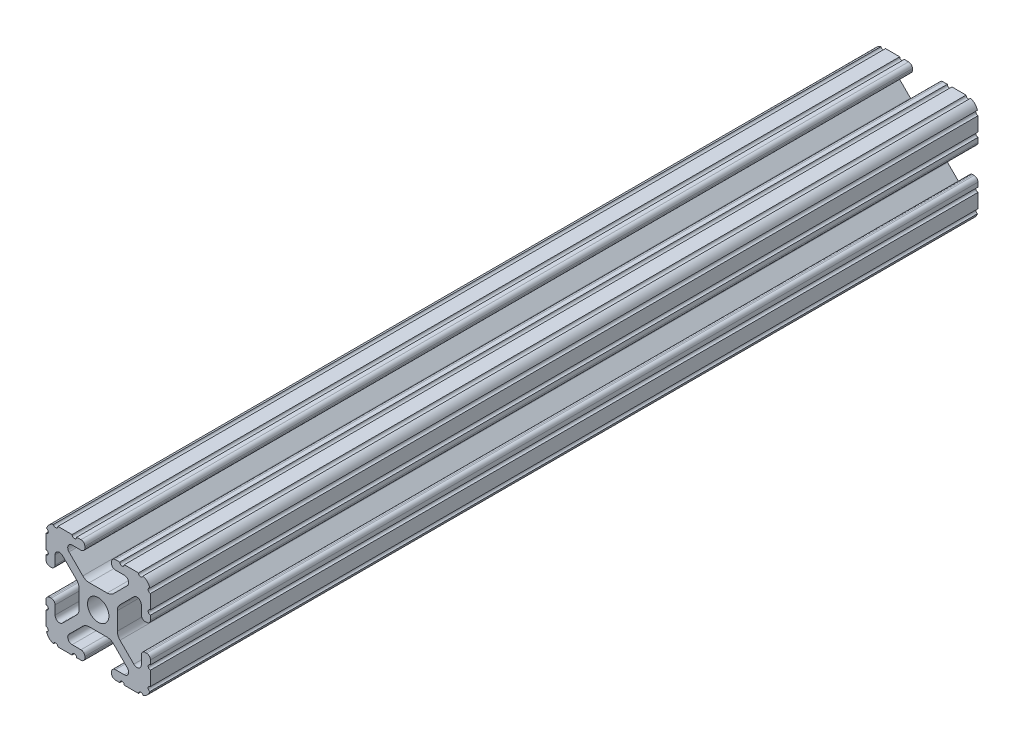
SolidWorks part; units mm, degrees
ref_plane "Front Plane" through (0, 0, 0) normal (0, 0, 1) x (1, 0, 0)
ref_plane "Top Plane" through (0, 0, 0) normal (0, 1, 0) x (1, 0, 0)
ref_plane "Right Plane" through (0, 0, 0) normal (1, 0, 0) x (0, 0, -1)
sketch "Sketch2" plane through (0, 0, 0) normal (0, 0, 1) x (1, 0, 0)
  line L0 (0, 12.7) -> (0, -12.7) construction
  line L1 (-12.7, 0) -> (12.7, 0) construction
  line L2 (3.2512, -12.7) -> (12.7, -12.7)
  line L3 (12.7, -12.7) -> (12.7, -3.2512)
  line L4 (3.2512, -12.7) -> (3.2512, -10.4902)
  line L5 (3.2512, -10.4902) -> (8.9276, -10.4902)
  line L6 (8.9276, -10.4902) -> (3.0856, -4.6482)
  line L7 (0, 0) -> (12.7, -12.7) construction
  line L8 (12.7, -3.2512) -> (10.4902, -3.2512)
  line L9 (10.4902, -3.2512) -> (10.4902, -8.9276)
  line L10 (10.4902, -8.9276) -> (4.6482, -3.0856)
  circle A0 centre (0, 0) radius 2.6035
  arc A1 (6.3485, -10.4902) -> (7.1039, -8.6665) centre (6.3485, -9.4219) ccw construction
  point P8 (0, -4.6482)
  dimension "Center Hole Diameter" = 5.207
  dimension "Rail Height" = 25.4
  dimension "Rail Width" = 25.4
  dimension "T-Slot Width" = 6.5024
  dimension "Slot Inner Width" = 14.8336
  dimension "Thickness" = 2.2098
  dimension "Slot Depth" = 5.842
  dimension "D1" = 2.2098
sketch "Sketch3" plane through (0, 0, 0) normal (1, 0, 0) x (0, 0, -1)
  line L0 (-100.6793, -12.7) -> (100.6793, -12.7) construction
  line L1 (-75.2793, 0) -> (75.2793, 0) construction
  line L4 (100.6793, 0) -> (-100.6793, 0) construction
sketch "Sketch4" plane through (0, 0, 0) normal (0, 0, 1) x (1, 0, 0)
  line L0 (4.1904, -12.7) -> (10.1173, -12.7)
  line L1 (3.2512, -12.7) -> (12.7, -12.7) construction
  line L2 (3.2512, -12.7) -> (3.2512, -10.4902) construction
  line L3 (3.2512, -10.4902) -> (8.9276, -10.4902) construction
  line L4 (3.2512, -11.4294) -> (3.2512, -11.7608)
  line L5 (4.1904, -10.4902) -> (6.3485, -10.4902)
  line L6 (0, -4.6482) -> (2.164, -4.6482)
  line L7 (8.9276, -10.4902) -> (3.0856, -4.6482) construction
  line L8 (3.7373, -5.2999) -> (7.1039, -8.6665)
  line L9 (12.7, -12.7) -> (12.7, -3.2512) construction
  line L10 (10.4902, -8.9276) -> (4.6482, -3.0856) construction
  line L11 (10.4902, -3.2512) -> (10.4902, -8.9276) construction
  line L12 (10.4902, -6.3485) -> (10.4902, -4.1904)
  line L13 (12.7, -3.2512) -> (10.4902, -3.2512) construction
  line L14 (11.4294, -3.2512) -> (11.7608, -3.2512)
  line L15 (12.7, -4.1904) -> (12.7, -10.1173)
  line L16 (8.6665, -7.1039) -> (5.2999, -3.7373)
  line L17 (4.6482, 0) -> (4.6482, -2.164)
  line L18 (-12.7, 0) -> (12.7, 0) construction
  line L19 (0, -4.6482) -> (0, -2.6035)
  line L20 (0, 12.7) -> (0, -12.7) construction
  line L21 (4.6482, 0) -> (2.6035, 0)
  arc A0 (3.2512, -11.7608) -> (4.1904, -12.7) centre (4.1904, -11.7608) ccw
  arc A2 (3.2512, -11.4294) -> (4.1904, -10.4902) centre (4.1904, -11.4294) cw
  arc A3 (6.3485, -10.4902) -> (7.1039, -8.6665) centre (6.3485, -9.4219) ccw
  arc A4 (2.164, -4.6482) -> (3.7373, -5.2999) centre (2.164, -6.8732) cw
  arc A5 (10.1173, -12.7) -> (12.7, -10.1173) centre (10.1173, -10.1173) ccw
  arc A6 (8.6665, -7.1039) -> (10.4902, -6.3485) centre (9.4219, -6.3485) ccw
  arc A7 (10.4902, -4.1904) -> (11.4294, -3.2512) centre (11.4294, -4.1904) cw
  arc A8 (11.7608, -3.2512) -> (12.7, -4.1904) centre (11.7608, -4.1904) cw
  arc A9 (5.2999, -3.7373) -> (4.6482, -2.164) centre (6.8732, -2.164) cw
  circle A10 centre (0, 0) radius 2.6035 construction
  arc A11 (0, -2.6035) -> (2.6035, 0) centre (0, 0) ccw
  dimension "D1" = 2.5827
  dimension "D2" = 2.225
  dimension "D3" = 0.9392
extrude "Boss-Extrude1" add sketch "Sketch4" along normal up to vertex (100.6793 mm away) from vertex at -100.6793 starting at point (0, -12.7, -100.6793)
sketch "Sketch5" plane through (0, 0, 0) normal (0, 0, 1) x (1, 0, 0)
  line L0 (3.2512, -12.7) -> (12.7, -12.7) construction
  line L1 (4.1904, -10.4902) -> (6.3485, -10.4902) construction
  line L3 (0, 0) -> (12.7, -12.7) construction
  line L4 (6.3485, -10.4902) -> (6.3485, -12.7) construction
  line L5 (8.9276, -10.4902) -> (3.0856, -4.6482) construction
  circle A0 centre (10.3562, -12.7) radius 0.5524
  circle A1 centre (5.796, -12.7) radius 0.5524
  circle A2 centre (12.7, -10.3562) radius 0.5524
  circle A3 centre (12.7, -5.796) radius 0.5524
  point P10 (5.2694, -10.4902)
  point P12 (9.4219, -6.3485)
  dimension "D1" = 1.1049
extrude "Cut-Extrude1" cut sketch "Sketch5" against normal through all both and the other way through all
mirror "Mirror1" about plane through (0, 0, 0) normal (1, 0, 0) of bodies 137 134
mirror "Mirror2" about plane through (0, 0, 0) normal (0, 1, 0) of bodies 135
equation "\"D1@Sketch2\"=\"Thickness@Sketch2\""
equation "\"D2@Sketch4\"=\"Slot Inner Width@Sketch2\"*0.15"
equation "\"D1@Sketch4\"=\"D3@Sketch4\"*2.75"
equation "\"D3@Sketch4\"=\"Thickness@Sketch2\"*0.425"
equation "\"D1@Sketch5\"=\"Thickness@Sketch2\"*0.5"
equation "\"D1@Boss-Extrude1\"=\"Length@Sketch3\""
